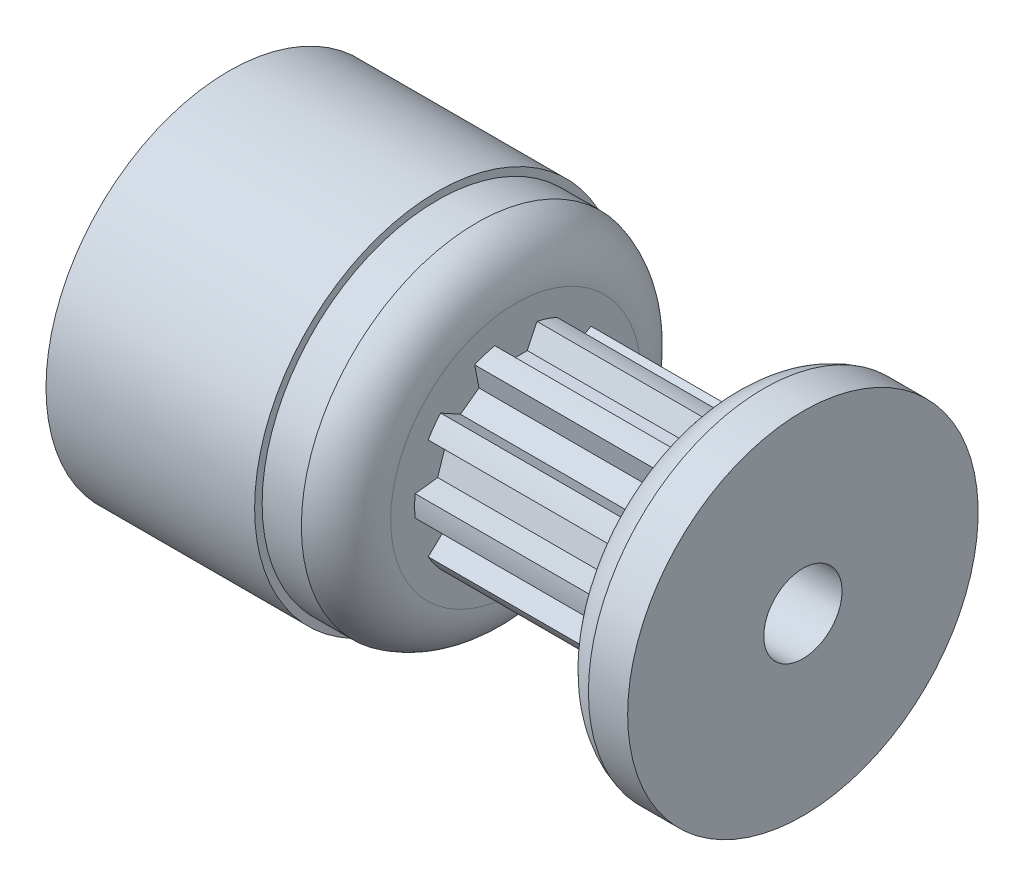
SolidWorks part; units mm, degrees
ref_plane "Front Plane" through (0, 0, 0) normal (0, 0, 1) x (1, 0, 0)
ref_plane "Top Plane" through (0, 0, 0) normal (0, 1, 0) x (1, 0, 0)
ref_plane "Right Plane" through (0, 0, 0) normal (1, 0, 0) x (0, 0, -1)
sketch "Sketch2" plane through (0, 0, 0) normal (1, 0, 0) x (0, 0, -1)
  line L3 (0, 0) -> (0, 2.413) construction
  line L6 (0, -2.921) -> (0, -3.2385) construction
  line L7 (-0.5715, 2.8645) -> (-0.3491, 2.3876)
  line L8 (0.5715, 2.8645) -> (0.3491, 2.3876)
  line L9 (-0.5715, 2.8645) -> (-0.6405, 3.0124)
  line L10 (0.5715, 2.8645) -> (0.6405, 3.0124)
  line L12 (-0.3491, 2.3876) -> (0.3491, 2.3876)
  line L14 (0, 2.921) -> (0, 3.2385) construction
  line L15 (0, 0) -> (0, -1.143) construction
  circle A0 centre (0, 0) radius 3.2385 construction
  circle A1 centre (0, 0) radius 2.413 construction
  circle A2 centre (0, 0) radius 2.921 construction
  arc A7 (0.6405, 3.0124) -> (-0.6405, 3.0124) centre (0, 0) ccw
  point P5 (0, 3.0798)
  dimension "D3" = 0.3175
  dimension "D1" = 50
sketch "Sketch1" plane through (0, 0, 0) normal (0, 0, 1) x (1, 0, 0)
  line L0 (-8.7376, 0) -> (8.7376, 0) construction
  line L1 (-8.7376, 1.1906) -> (8.7376, 1.1906)
  line L2 (-8.7376, 1.1906) -> (-8.7376, 5.5626)
  line L3 (-2.3876, 5.334) -> (-1.1938, 5.334)
  line L4 (0, 3.2385) -> (0, 3.81)
  line L5 (0, 4.3815) -> (0, 3.2385) construction
  line L6 (0, 3.2385) -> (6.35, 3.2385)
  line L7 (6.35, 3.2385) -> (6.35, 3.81)
  line L8 (6.35, 3.2385) -> (8.7376, 3.2385) construction
  line L9 (7.5438, 5.334) -> (8.7376, 5.334)
  line L10 (8.7376, 5.334) -> (8.7376, 1.1906)
  line L11 (7.5438, 3.2385) -> (7.5438, 5.334) construction
  line L12 (-5.5626, 5.5626) -> (-5.5626, 1.1906) construction
  line L13 (-2.3876, 5.334) -> (-2.3876, 5.5626)
  line L14 (-2.3876, 5.5626) -> (-8.7376, 5.5626)
  arc A0 (6.35, 3.81) -> (7.5438, 5.334) centre (7.9197, 3.81) cw
  arc A1 (0, 3.81) -> (-1.1938, 5.334) centre (-1.5697, 3.81) ccw
  dimension "Bore Size" = 2.3813
  dimension "Overall Width" = 17.4752
  dimension "Inside Width" = 6.35
  dimension "OD" = 10.668
  dimension "D2" = 6.477
  dimension "D3" = 1.143
  dimension "D4" = 0.5715
  dimension "Outside Width" = 11.1252
revolve "Revolve1" add sketch "Sketch1" angle 360 mid plane about L0
sketch "Sketch4" plane through (0, 0, 0) normal (1, 0, 0) x (0, 0, -1)
  circle A0 centre (0, 0) radius 3.0798
  circle A2 centre (0, 0) radius 3.2385
  circle A3 centre (0, 0) radius 3.2385 construction
extrude "Cut-Extrude2" cut sketch "Sketch4" along normal up to surface (6.35 mm away) up to face at (6.35, 0, 3.2385)
sketch "Sketch3" plane through (0, 0, 0) normal (1, 0, 0) x (0, 0, -1)
  line L2 (-0.5715, 2.8645) -> (-0.3491, 2.3876) construction
  line L3 (-0.3491, 2.3876) -> (0.3491, 2.3876) construction
  line L4 (0.5715, 2.8645) -> (0.3491, 2.3876) construction
  line L5 (-0.6405, 3.0124) -> (-0.3491, 2.3876)
  line L6 (-0.3491, 2.3876) -> (0.3491, 2.3876)
  line L7 (0.6405, 3.0124) -> (0.3491, 2.3876)
  arc A1 (0.6405, 3.0124) -> (-0.6405, 3.0124) centre (0, 0) ccw construction
  arc A2 (0.6405, 3.0124) -> (-0.6405, 3.0124) centre (0, 0) ccw
extrude "Cut-Extrude1" cut sketch "Sketch3" along normal up to surface (6.35 mm away) up to face at (6.35, 0, 3.81)
pattern_circular "CirPattern1" count 10 over 360 about axis through (0, 0, 0) along (1, 0, 0) of "Cut-Extrude1"
sketch "Sketch5" plane through (0, 0, 0) normal (0, 0, 1) x (1, 0, 0)
  line L1 (6.35, 3.81) -> (6.35, -3.81) construction
  point P0 (6.35, 0)
equation "\"D3@Sketch2\" = (\"hs@Sketch2\"-\"ht@Sketch2\")/2"
equation "\"D2@Sketch1\" = \"PD@Sketch2\""
equation "\"D3@Sketch1\" = \"hs@Sketch2\""
equation "\"D4@Sketch1\" = \"D3@Sketch1\"/2"
